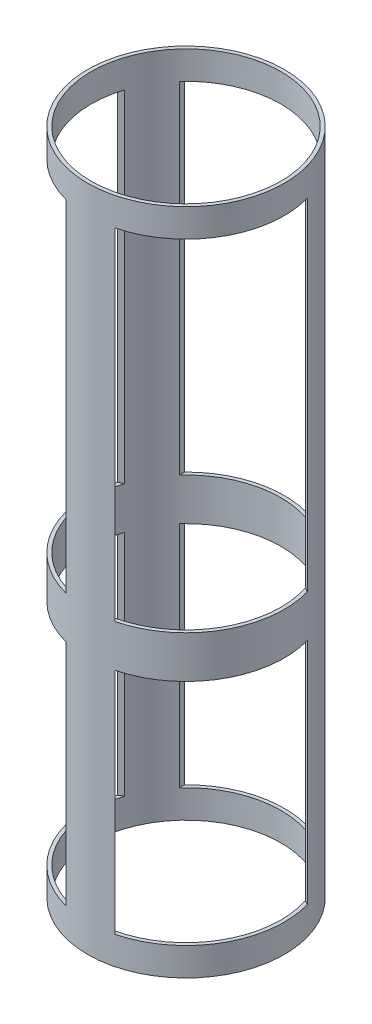
SolidWorks part; units mm, degrees
material "6061-T6 (SS)"
ref_plane "Front Plane" through (0, 0, 0) normal (0, 0, 1) x (1, 0, 0)
ref_plane "Top Plane" through (0, 0, 0) normal (0, 1, 0) x (1, 0, 0)
ref_plane "Right Plane" through (0, 0, 0) normal (1, 0, 0) x (0, 0, -1)
sketch "Sketch1" plane through (0, 0, 0) normal (0, 1, 0) x (1, 0, 0)
  circle A0 centre (0, 0) radius 88.9
  circle A1 centre (0, 0) radius 85.725
  dimension "D1" = 177.8
  dimension "D2" = 171.45
extrude "Boss-Extrude1" add sketch "Sketch1" along normal mid plane 603.25
sketch "Sketch2" plane through (0, 0, 0) normal (0, 0, 1) x (1, 0, 0)
  line L0 (88.9, -301.625) -> (88.9, 301.625) construction
  line L5 (-88.9, -301.625) -> (88.9, -301.625) construction
  line L6 (63.5, -276.225) -> (-63.5, -276.225)
  line L7 (-88.9, 301.625) -> (-88.9, -301.625) construction
  line L9 (63.5, -276.225) -> (63.5, -69.723)
  line L10 (63.5, -69.723) -> (-63.5, -69.723)
  line L11 (-63.5, -276.225) -> (-63.5, -69.723)
  line L12 (85.725, 301.625) -> (-85.725, 301.625) construction
  line L13 (63.5, -31.623) -> (-63.5, -31.623)
  line L14 (63.5, -31.623) -> (63.5, 276.225)
  line L15 (63.5, 276.225) -> (-63.5, 276.225)
  line L16 (-63.5, -31.623) -> (-63.5, 276.225)
  dimension "D1" = 25.4
  dimension "D2" = 25.4
  dimension "D3" = 25.4
  dimension "D4" = 231.902
  dimension "D5" = 25.4
  dimension "D6" = 38.1
extrude "Cut-Extrude1" cut sketch "Sketch2" against normal up to surface (62.217 mm away)
pattern_circular "CirPattern1" count 3 over 360 about axis through (0, 0, 0) along (0, 1, 0) of "Cut-Extrude1"
ref_plane "Plane1" through (0, 0, 88.9) normal (0, 0, 1) x (1, 0, 0)
sketch "Sketch3" plane through (0, 0, 88.9) normal (0, 0, 1) x (1, 0, 0)
  line L0 (0, -97.79) -> (0, 97.79) construction
  line L1 (88.9, 301.625) -> (-88.9, 301.625) construction
  circle A0 centre (0, 295.275) radius 1.4351
  dimension "D1" = 2.8702
  dimension "D2" = 6.35
extrude "Cut-Extrude2" [suppressed] cut sketch "Sketch3" against normal blind 25.908
pattern_circular "CirPattern2" [suppressed] count 12 over 360
mirror "Mirror1" [suppressed] about plane through (0, 0, 0) normal (0, 1, 0)
sketch "Sketch4" [suppressed] plane through (0, 0, 88.9) normal (0, 0, 1) x (1, 0, 0)
  line L0 (0, -97.79) -> (0, 97.79) construction
  circle A0 centre (0, -225.425) radius 1.4351
  circle A1 centre (0, -212.725) radius 1.4351
  circle A2 centre (0, -295.275) radius 1.4351 construction
  circle A3 centre (0, -149.225) radius 1.4351
  circle A4 centre (0, -136.525) radius 1.4351
  dimension "D1" = 69.85
  dimension "D2" = 2.8702
  dimension "D3" = 12.7
  dimension "D4" = 2.8702
  dimension "D5" = 63.5
  dimension "D6" = 12.7
  dimension "D7" = 2.8702
  dimension "D8" = 2.8702
extrude "Cut-Extrude3" [suppressed] cut sketch "Sketch4" against normal blind 34.798
pattern_circular "CirPattern3" [suppressed] count 3 over 360
sketch "Sketch5" [suppressed] plane through (0, 0, 88.9) normal (0, 0, 1) x (1, 0, 0)
  line L0 (0, -97.79) -> (0, 97.79) construction
  line L1 (-22.1315, -31.623) -> (-88.9, -31.623) construction
  line L2 (-88.9, -69.723) -> (-22.1315, -69.723) construction
  line L3 (88.9, -31.623) -> (22.1315, -31.623) construction
  circle A0 centre (0, -50.673) radius 1.4351
  circle A1 centre (0, 73.025) radius 1.4351
  circle A2 centre (0, 177.927) radius 1.4351
  circle A3 centre (0, 295.275) radius 1.4351 construction
  circle A4 centre (0, -37.973) radius 1.4351
  circle A5 centre (0, -63.373) radius 1.4351
  dimension "D1" = 2.8702
  dimension "D3" = 117.348
  dimension "D5" = 2.8702
  dimension "D6" = 2.8702
  dimension "D4" = 123.698
  dimension "D7" = 2.8702
  dimension "D8" = 2.8702
  dimension "D9" = 6.35
  dimension "D10" = 6.35
  dimension "D2" = 19.05
extrude "Cut-Extrude4" [suppressed] cut sketch "Sketch5" against normal blind 87.63
pattern_circular "CirPattern4" [suppressed] count 12 over 360
